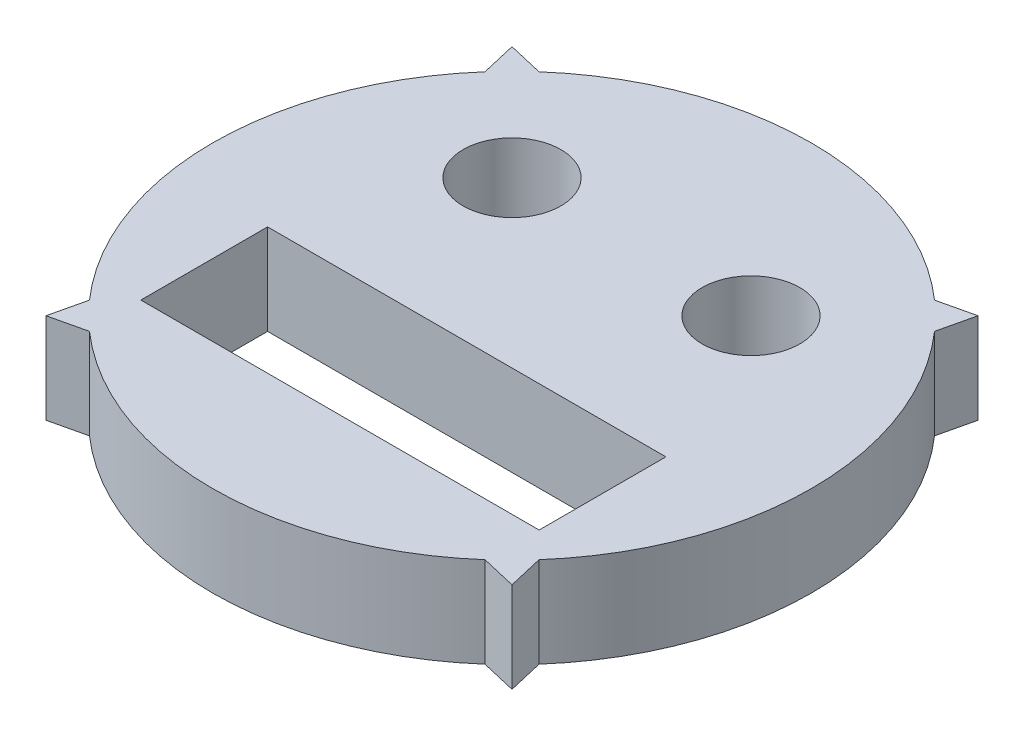
SolidWorks part; units mm, degrees
ref_plane "Front Plane" through (0, 0, 0) normal (0, 0, 1) x (1, 0, 0)
ref_plane "Top Plane" through (0, 0, 0) normal (0, 1, 0) x (1, 0, 0)
ref_plane "Right Plane" through (0, 0, 0) normal (1, 0, 0) x (0, 0, -1)
sketch "Sketch1" plane through (0, 0, 0) normal (0, 1, 0) x (1, 0, 0)
  line L0 (13.8701, 15.7677) -> (16.3439, 16.3439)
  line L1 (16.3439, 16.3439) -> (15.7677, 13.8701)
  line L2 (15.7677, -13.8701) -> (16.3439, -16.3439)
  line L3 (16.3439, -16.3439) -> (13.8701, -15.7677)
  line L4 (-13.8701, -15.7677) -> (-16.3439, -16.3439)
  line L5 (-16.3439, -16.3439) -> (-15.7677, -13.8701)
  line L6 (-15.7677, 13.8701) -> (-16.3439, 16.3439)
  line L7 (-16.3439, 16.3439) -> (-13.8701, 15.7677)
  line L8 (16.3439, 16.3439) -> (0, 0) construction
  line L9 (0, 0) -> (21, 0) construction
  line L10 (-20.7586, -3.175) -> (20.7586, -3.175) construction
  line L12 (-13.97, -3.175) -> (13.97, -3.175)
  line L13 (-13.97, -3.175) -> (-13.97, -12.065)
  line L14 (-13.97, -12.065) -> (13.97, -12.065)
  line L15 (13.97, -3.175) -> (13.97, -12.065)
  arc A0 (13.8701, 15.7677) -> (-13.8701, 15.7677) centre (0, 0) ccw
  arc A1 (15.7677, -13.8701) -> (15.7677, 13.8701) centre (0, 0) ccw
  arc A2 (-13.8701, -15.7677) -> (13.8701, -15.7677) centre (0, 0) ccw
  arc A3 (-15.7677, 13.8701) -> (-15.7677, -13.8701) centre (0, 0) ccw
  circle A7 centre (-8.382, 8.382) radius 3.429
  circle A8 centre (8.382, 8.382) radius 3.429
  point P18 (0, 0)
  point P28 (0, -12.065)
  dimension "D1" = 42
  dimension "D8" = 6.858
  dimension "D2" = 2.54
  dimension "D3" = 2.54
  dimension "D5" = 23.1137
  dimension "D6" = 45
  dimension "D10" = 3.175
  dimension "D11" = 8.89
  dimension "D12" = 27.94
  dimension "D14" = 8.382
  dimension "D15" = 8.382
  dimension "D16" = 2
  dimension "D4" = 4
extrude "Boss-Extrude1" add sketch "Sketch1" along normal blind 6.35
